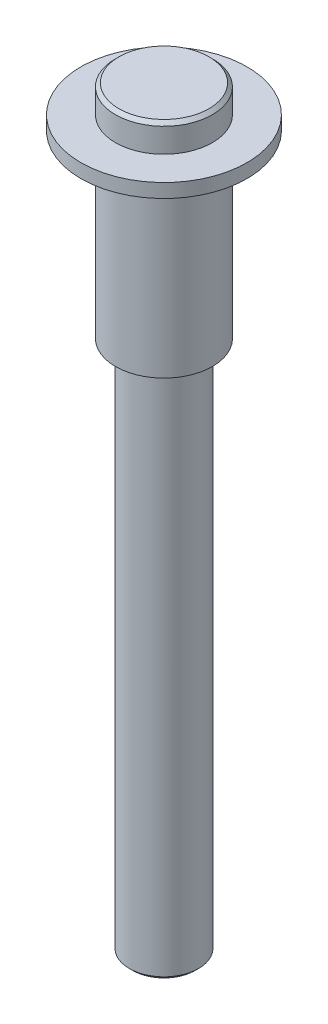
SolidWorks part; units mm, degrees
ref_plane "Front Plane" through (0, 0, 0) normal (0, 0, 1) x (1, 0, 0)
ref_plane "Top Plane" through (0, 0, 0) normal (0, 1, 0) x (1, 0, 0)
ref_plane "Right Plane" through (0, 0, 0) normal (1, 0, 0) x (0, 0, -1)
sketch "Sketch2" plane through (0, 0, 0) normal (0, 1, 0) x (1, 0, 0)
  circle A0 centre (0, 0) radius 3.5
  dimension "D1" = 7
extrude "Boss-Extrude1" add sketch "Sketch2" along normal blind 16
chamfer "Chamfer1" distance 0.25 angle 45 1 edges at (0, 16, 3.5)
sketch "Sketch3" plane through (0, 0, 0) normal (0, -1, 0) x (1, 0, 0)
  circle A0 centre (0, 0) radius 2.5
  dimension "D1" = 5
extrude "Boss-Extrude2" add sketch "Sketch3" along normal blind 38.4
chamfer "Chamfer2" distance 0.25 angle 45 1 edges at (0, -38.4, -2.5)
ref_plane "Plane1" through (0, 14, 0) normal (0, 1, 0) x (1, 0, 0)
sketch "Sketch4" plane through (0, 14, 0) normal (0, 1, 0) x (1, 0, 0)
  circle A0 centre (0, 0) radius 6
  dimension "D1" = 12
extrude "Boss-Extrude3" add sketch "Sketch4" against normal blind 1
